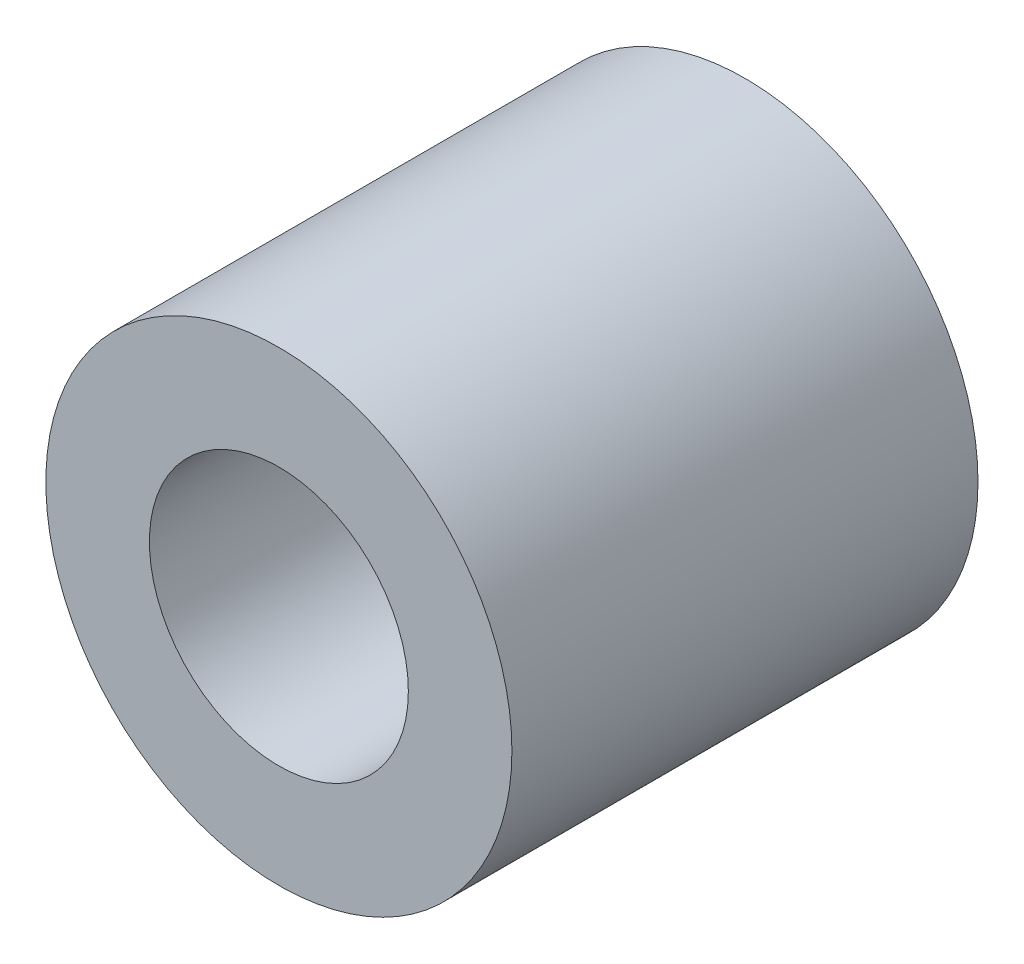
SolidWorks part; units mm, degrees
ref_plane "Plane1" through (0, 0, 0) normal (0, 0, 1) x (1, 0, 0)
ref_plane "Plane2" through (0, 0, 0) normal (0, 1, 0) x (1, 0, 0)
ref_plane "Plane3" through (0, 0, 0) normal (1, 0, 0) x (0, 0, -1)
other "Configuration Table"
sketch "Sketch1" plane through (0, 0, 0) normal (0, 0, 1) x (1, 0, 0)
  circle A0 centre (0, 0) radius 4.5
  dimension "D1" = 9
extrude "insert shape" add sketch "Sketch1" along normal blind 9
sketch "Sketch2" plane through (0, 0, 9) normal (0, 0, 1) x (1, 0, 0)
  line L0 (0, 0) -> (0, 5.7005) construction
  line L1 (-0.05, 4.4997) -> (0, 4.5997)
  line L2 (0.05, 4.4997) -> (0, 4.5997)
  line L3 (-0.05, 4.4997) -> (0.05, 4.4997)
  circle A0 centre (0, 0) radius 4.5 construction
  dimension "D1" = 0.1
  dimension "D2" = 0.1
extrude "grip ribs" [suppressed] add sketch "Sketch2" along normal up to surface (9 mm away)
pattern_circular "copy grip ribs" [suppressed] count 24 every 15
sketch "Sketch3" plane through (0, 0, 9) normal (0, 0, 1) x (1, 0, 0)
  circle A0 centre (0, 0) radius 2.5
  dimension "D1" = 5
extrude "center hole" cut sketch "Sketch3" against normal blind 4.3
sketch "Sketch4" plane through (0, 0, 4.7) normal (0, 0, 1) x (1, 0, 0)
  circle A0 centre (0, 0) radius 1.75
  dimension "D1" = 3.5
extrude "tapped hole" cut sketch "Sketch4" against normal up to next
cosmetic thread "Cosmetic Thread4" parameters "D1"=4.7, "D2"=5
